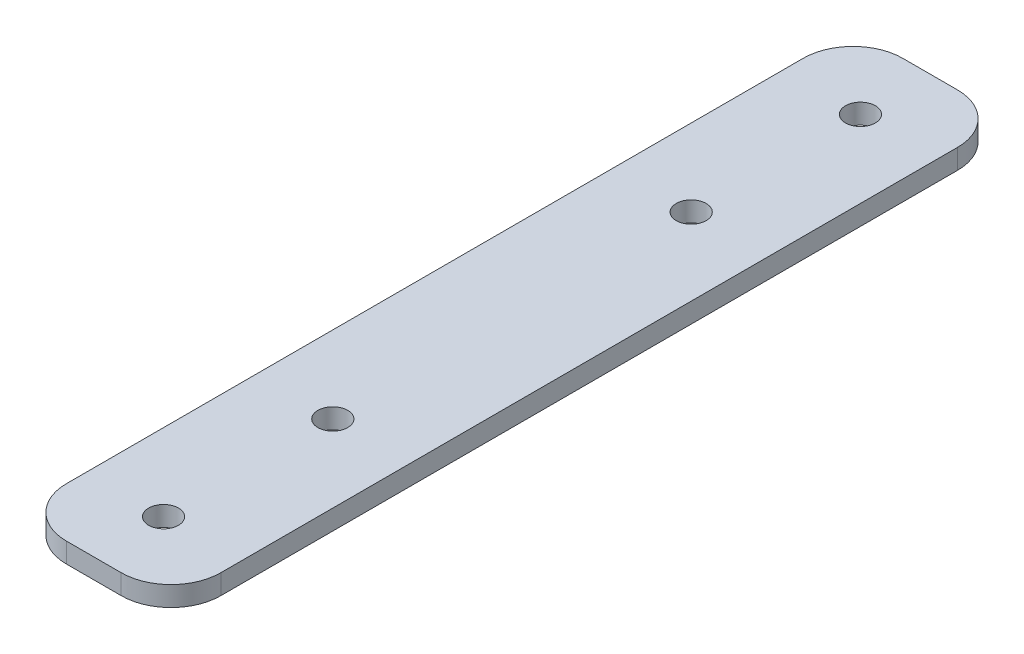
SolidWorks part; units mm, degrees
material "3.0205 (EN-AW 1200)"
ref_plane "Plan de face" through (0, 0, 0) normal (0, 0, 1) x (1, 0, 0)
ref_plane "Plan de dessus" through (0, 0, 0) normal (0, 1, 0) x (1, 0, 0)
ref_plane "Plan de droite" through (0, 0, 0) normal (1, 0, 0) x (0, 0, -1)
sketch "Esquisse1" plane through (0, 0, 0) normal (0, 0, 1) x (1, 0, 0)
  line L1 (0, 0) -> (15.5, 0)
  dimension "D2" = 15.5
extrude "Extru.-Mince1" add sketch "Esquisse1" along normal blind 84 thin thin type one direction reverse wall 2
sketch "Esquisse2" plane through (0, 2, 0) normal (0, 1, 0) x (1, 0, 0)
  line L0 (0, -42) -> (15.5, -42) construction
  line L1 (0, -84) -> (0, 0) construction
  line L2 (15.5, -84) -> (15.5, 0) construction
  line L3 (0, 0) -> (15.5, 0) construction
  circle A0 centre (7.75, -24) radius 1.5
  circle A1 centre (7.75, -7) radius 1.5
  circle A2 centre (7.75, -77) radius 1.5
  circle A3 centre (7.75, -60) radius 1.5
  point P11 (7.75, -42)
  dimension "D1" = 36
  dimension "D2" = 70
  dimension "D3" = 17
  dimension "D4" = 7
  dimension "D5" = 3
extrude "Enlèv. mat.-Extru.1" cut sketch "Esquisse2" against normal through all
fillet "Congé1" radius 5 4 edges at (0, 1, 0) (15.5, 1, 84) (15.5, 1, 0) (0, 1, 84)
